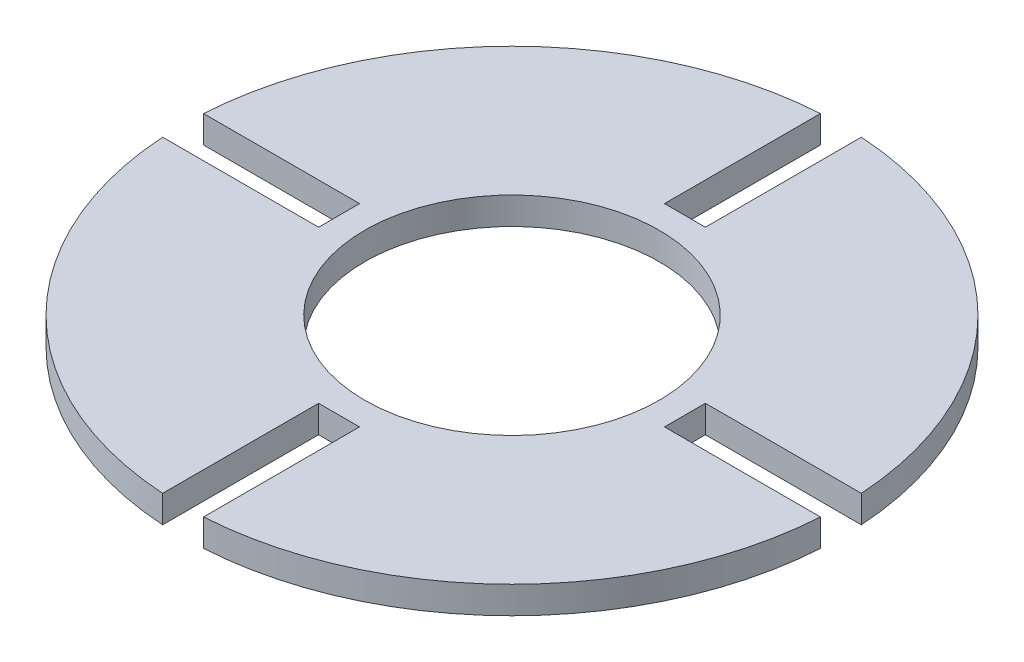
SolidWorks part; units mm, degrees
ref_plane "Front Plane" through (0, 0, 0) normal (0, 0, 1) x (1, 0, 0)
ref_plane "Top Plane" through (0, 0, 0) normal (0, 1, 0) x (1, 0, 0)
ref_plane "Right Plane" through (0, 0, 0) normal (1, 0, 0) x (0, 0, -1)
sketch "Sketch1" plane through (0, 0, 0) normal (0, 1, 0) x (1, 0, 0)
  line L0 (0, 56.2442) -> (0, -47.727) construction
  line L1 (-38.3039, 0) -> (49.8794, 0) construction
  line L3 (-1.5, 24.1034) -> (-1.5, 12.6734)
  line L4 (-1.5, 12.6734) -> (1.5, 12.6734)
  line L5 (1.5, 12.6734) -> (1.5, 24.1034)
  line L6 (12.6734, -1.5) -> (24.1034, -1.5)
  line L7 (24.1034, 1.5) -> (12.6734, 1.5)
  line L8 (12.6734, 1.5) -> (12.6734, -1.5)
  line L9 (-1.5, -12.6734) -> (-1.5, -24.1034)
  line L10 (1.5, -24.1034) -> (1.5, -12.6734)
  line L11 (1.5, -12.6734) -> (-1.5, -12.6734)
  line L12 (-12.6734, 1.5) -> (-24.1034, 1.5)
  line L13 (-24.1034, -1.5) -> (-12.6734, -1.5)
  line L14 (-12.6734, -1.5) -> (-12.6734, 1.5)
  arc A0 (-1.5, 24.1034) -> (-24.1034, 1.5) centre (0, 0) ccw
  arc A1 (24.1034, 1.5) -> (1.5, 24.1034) centre (0, 0) ccw
  arc A2 (1.5, -24.1034) -> (24.1034, -1.5) centre (0, 0) ccw
  arc A3 (-24.1034, -1.5) -> (-1.5, -24.1034) centre (0, 0) ccw
  circle A4 centre (0, 0) radius 10.795
  point P26 (0, 0)
  dimension "D1" = 48.3
  dimension "D6" = 21.59
  dimension "D2" = 3
  dimension "D3" = 11.43
  dimension "D4" = 3
  dimension "D5" = 4
extrude "Boss-Extrude1" add sketch "Sketch1" along normal blind 2
